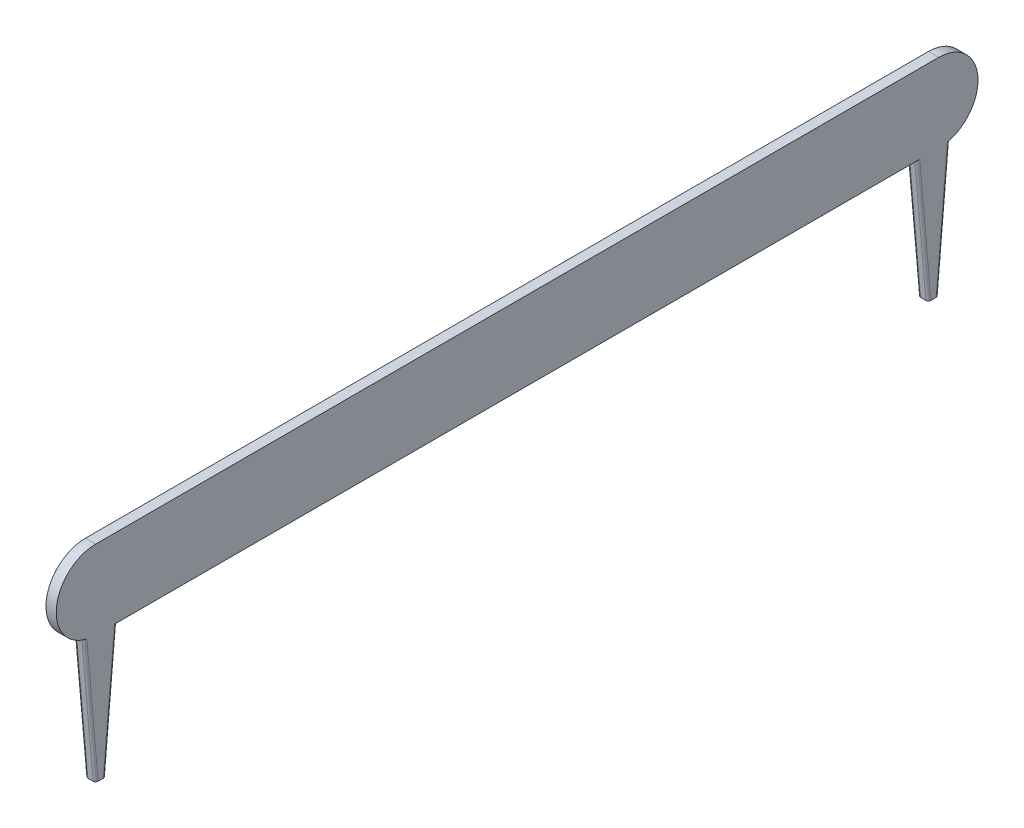
SolidWorks part; units mm, degrees
material "Malleable Cast Iron"
ref_plane "Front Plane" through (0, 0, 0) normal (0, 0, 1) x (1, 0, 0)
ref_plane "Top Plane" through (0, 0, 0) normal (0, 1, 0) x (1, 0, 0)
ref_plane "Right Plane" through (0, 0, 0) normal (1, 0, 0) x (0, 0, -1)
sketch "Sketch1" plane through (0, 0, 0) normal (1, 0, 0) x (0, 0, -1)
  line L2 (-824.175, -50) -> (824.175, -50)
  line L3 (-824.175, 104) -> (824.175, 104)
  arc A2 (-824.175, 104) -> (-824.175, -50) centre (-824.175, 27) ccw
  arc A3 (824.175, 104) -> (824.175, -50) centre (824.175, 27) cw
extrude "Boss-Extrude1" add sketch "Sketch1" along normal blind 20 contours A2 L2 A3 L3
sketch "Sketch2" plane through (0, -50, 0) normal (0, -1, 0) x (1, 0, 0)
  line L0 (20, 824.175) -> (20, -824.175) construction
  line L1 (0, 824.175) -> (20, 824.175)
  line L2 (0, 824.175) -> (0, 804.175)
  line L3 (0, 804.175) -> (20, 804.175)
  line L4 (20, 824.175) -> (20, 804.175)
  dimension "D1" = 20
extrude "Boss-Extrude2" add sketch "Sketch2" along normal blind 250
draft "Draft5" type of draft neutral plane draft angle 5 faces to draft 2 face at (10, -175, 824.175) face at (10, -175, 804.175) neutral plane through (0, -300, 0) neutral plane normal (0, -1, 0) parameters "D1"=5
fillet "Fillet1" radius 5 4 edges at (0, -175, 793.2389) (0, -173.3716, 835.2535) (20, -175, 793.2389) (20, -173.3716, 835.2535)
mirror "Mirror2" about plane through (0, 0, 0) normal (0, 0, 1) of "Fillet1", "Draft5", "Boss-Extrude2"
